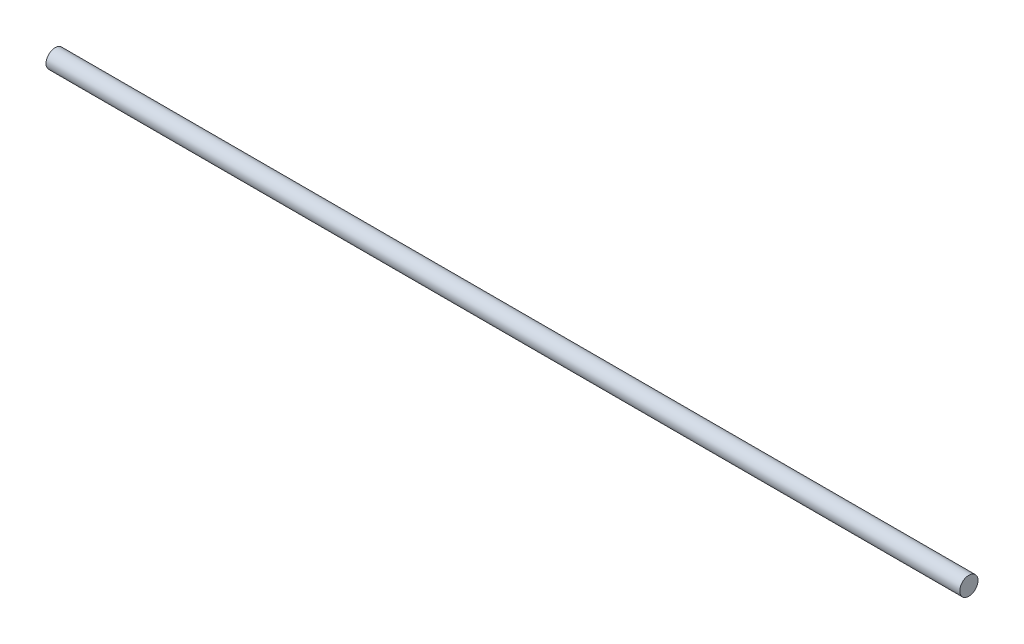
SolidWorks part; units mm, degrees
ref_plane "Front Plane" through (0, 0, 0) normal (0, 0, 1) x (1, 0, 0)
ref_plane "Top Plane" through (0, 0, 0) normal (0, 1, 0) x (1, 0, 0)
ref_plane "Right Plane" through (0, 0, 0) normal (1, 0, 0) x (0, 0, -1)
sketch "Sketch6" plane through (0, 0, 0) normal (1, 0, 0) x (0, 0, -1)
  circle A0 centre (0, 0) radius 1.524
  dimension "D1" = 3.048
extrude "Boss-Extrude2" add sketch "Sketch6" along normal mid plane 152.4 separate body
equation "\"D3@Sketch1\"=\"Hole Spacing@Sketch1\""
equation "\"D1@Sketch1\"=\"Hole to End 1@Sketch1\""
equation "\"D2@Sketch1\"=\"Hole to End 2@Sketch1\""
equation "\"D4@Sketch1\"=\"Hole Spacing@Sketch1\""
equation "\"D6@Sketch1\"=\"D4@Sketch1\""
equation "\"D1@Boss-Extrude1\"=\"Leaf Height@Sketch1\""
equation "\"D1@Sketch4\"=\"Knuckle Length@Sketch1\""
equation "\"D3@LPattern1\"=\"Knuckle Length@Sketch1\"*2"
equation "\"D1@Sketch6\"=\"Pin Diameter@Sketch2\""
equation "\"D1@Boss-Extrude2\"=\"Leaf Height@Sketch1\""
equation "\"D1@Sketch7\"=\"Pin Diameter@Sketch2\""
equation "\"D2@Sketch7\"=\"Overall Width@Sketch1\""
equation "\"D3@Sketch7\"=\"Leaf Thickness@Sketch2\""
